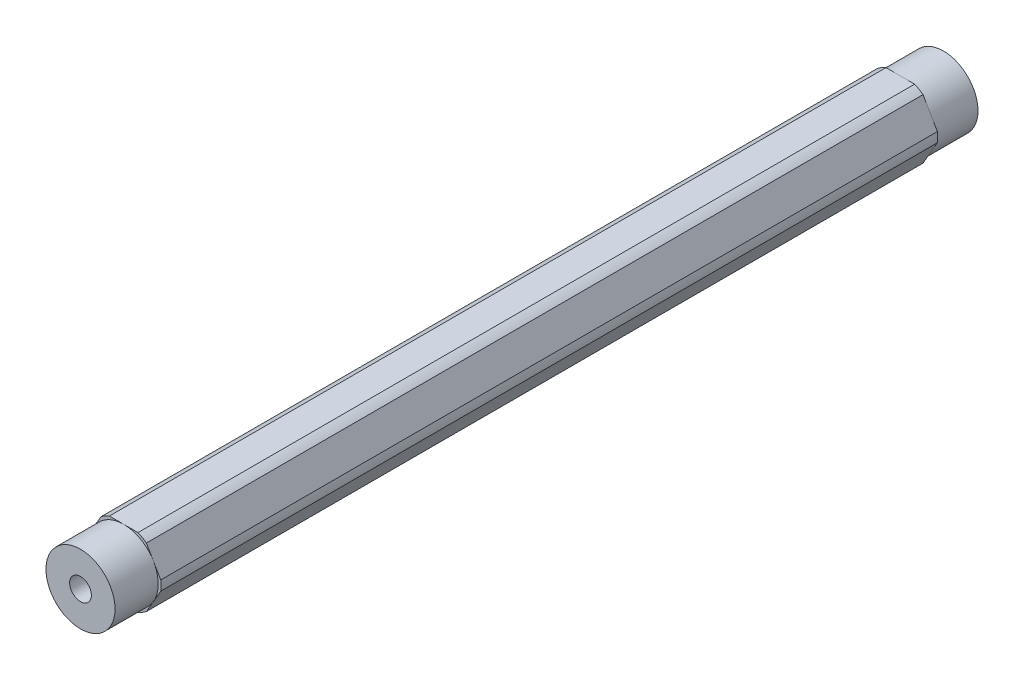
SolidWorks part; units mm, degrees
material "6061-T6 (SS)"
ref_plane "Front Plane" through (0, 0, 0) normal (0, 0, 1) x (1, 0, 0)
ref_plane "Top Plane" through (0, 0, 0) normal (0, 1, 0) x (1, 0, 0)
ref_plane "Right Plane" through (0, 0, 0) normal (1, 0, 0) x (0, 0, -1)
sketch "Sketch1" plane through (0, 0, 0) normal (0, 0, 1) x (1, 0, 0)
  line L1 (3.6662, 6.35) -> (-3.6662, 6.35)
  line L2 (-3.6662, 6.35) -> (-7.3323, 0)
  line L3 (-7.3323, 0) -> (-3.6662, -6.35)
  line L4 (-3.6662, -6.35) -> (3.6662, -6.35)
  line L5 (3.6662, -6.35) -> (7.3323, 0)
  line L6 (7.3323, 0) -> (3.6662, 6.35)
  circle A0 centre (0, 0) radius 6.35 construction
  circle A1 centre (0, 0) radius 2
  circle A2 centre (0, 0) radius 6.875
  point P1 (0, 6.35)
  dimension "D2" = 13.75
  dimension "D3" = 4
  dimension "D1" = 12.7
extrude "Boss-Extrude1" add sketch "Sketch1" along normal mid plane 142.8242 contours L6 A2 L1 L2 L3 L4 L5 A1
sketch "Sketch4" plane through (0, 0, 71.4121) normal (0, 0, 1) x (1, 0, 0)
  circle A0 centre (0, 0) radius 6.35
  circle A1 centre (0, 0) radius 2 construction
  circle A2 centre (0, 0) radius 2
  dimension "D1" = 12.7
extrude "Boss-Extrude2" add sketch "Sketch4" along normal blind 7.9375
mirror "Mirror1" about plane through (0, 0, 0) normal (0, 0, 1) of "Boss-Extrude2"
equation "\"D2@Sketch1\"=13.75mm"
equation "\"D3@Sketch1\"=4mm"
